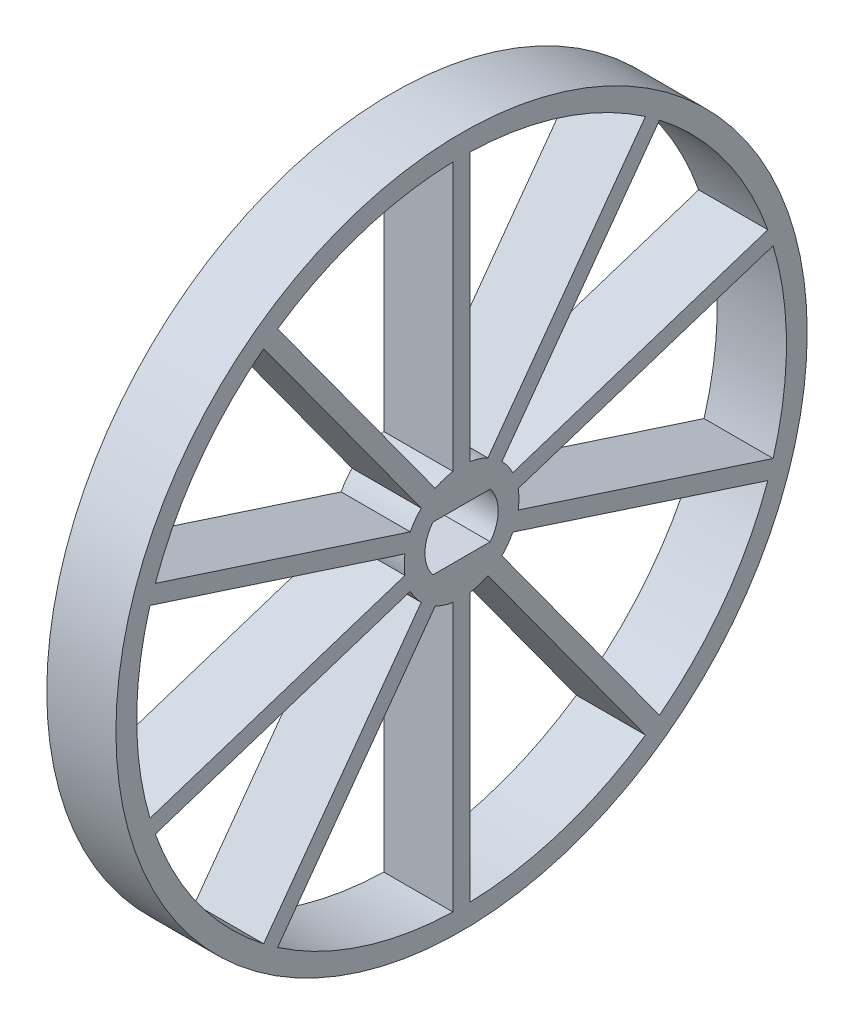
SolidWorks part; units mm, degrees
ref_plane "Front Plane" through (0, 0, 0) normal (0, 0, 1) x (1, 0, 0)
ref_plane "Top Plane" through (0, 0, 0) normal (0, 1, 0) x (1, 0, 0)
ref_plane "Right Plane" through (0, 0, 0) normal (1, 0, 0) x (0, 0, -1)
sketch "Sketch1" plane through (0, 0, 0) normal (1, 0, 0) x (0, 0, -1)
  line L0 (0, 0) -> (0, 27.6652) construction
  line L1 (-2.65, -1.65) -> (2.65, -1.65)
  line L2 (-2.65, -1.65) -> (-2.65, 1.65)
  line L3 (-2.65, 1.65) -> (2.65, 1.65)
  line L4 (2.65, -1.65) -> (2.65, 1.65)
  line L5 (-2.65, -1.65) -> (2.65, 1.65) construction
  line L6 (-2.65, 1.65) -> (2.65, -1.65) construction
  line L8 (-0.625, 3.8326) -> (0.625, 3.8326)
  line L9 (-0.625, 3.8326) -> (-0.625, 23.8326)
  line L10 (-0.625, 23.8326) -> (0.625, 23.8326)
  line L11 (0.625, 3.8326) -> (0.625, 23.8326)
  line L12 (-0.625, 3.8326) -> (0.625, 23.8326) construction
  line L13 (-0.625, 23.8326) -> (0.625, 3.8326) construction
  line L57 (1.7471, 3.468) -> (13.5028, 19.6484)
  line L58 (1.7471, 3.468) -> (2.7584, 2.7333)
  line L59 (2.7584, 2.7333) -> (14.5141, 18.9136)
  line L60 (13.5028, 19.6484) -> (14.5141, 18.9136)
  line L61 (3.4519, 1.7788) -> (22.473, 7.9591)
  line L62 (3.4519, 1.7788) -> (3.8382, 0.5899)
  line L63 (3.8382, 0.5899) -> (22.8593, 6.7703)
  line L64 (22.473, 7.9591) -> (22.8593, 6.7703)
  line L65 (3.8382, -0.5899) -> (22.8593, -6.7703)
  line L66 (3.8382, -0.5899) -> (3.4519, -1.7788)
  line L67 (3.4519, -1.7788) -> (22.473, -7.9591)
  line L68 (22.8593, -6.7703) -> (22.473, -7.9591)
  line L69 (2.7584, -2.7333) -> (14.5141, -18.9136)
  line L70 (2.7584, -2.7333) -> (1.7471, -3.468)
  line L71 (1.7471, -3.468) -> (13.5028, -19.6484)
  line L72 (14.5141, -18.9136) -> (13.5028, -19.6484)
  line L73 (0.625, -3.8326) -> (0.625, -23.8326)
  line L74 (0.625, -3.8326) -> (-0.625, -3.8326)
  line L75 (-0.625, -3.8326) -> (-0.625, -23.8326)
  line L76 (0.625, -23.8326) -> (-0.625, -23.8326)
  line L77 (-1.7471, -3.468) -> (-13.5028, -19.6484)
  line L78 (-1.7471, -3.468) -> (-2.7584, -2.7333)
  line L79 (-2.7584, -2.7333) -> (-14.5141, -18.9136)
  line L80 (-13.5028, -19.6484) -> (-14.5141, -18.9136)
  line L81 (-3.4519, -1.7788) -> (-22.473, -7.9591)
  line L82 (-3.4519, -1.7788) -> (-3.8382, -0.5899)
  line L83 (-3.8382, -0.5899) -> (-22.8593, -6.7703)
  line L84 (-22.473, -7.9591) -> (-22.8593, -6.7703)
  line L85 (-3.8382, 0.5899) -> (-22.8593, 6.7703)
  line L86 (-3.8382, 0.5899) -> (-3.4519, 1.7788)
  line L87 (-3.4519, 1.7788) -> (-22.473, 7.9591)
  line L88 (-22.8593, 6.7703) -> (-22.473, 7.9591)
  line L89 (-2.7584, 2.7333) -> (-14.5141, 18.9136)
  line L90 (-2.7584, 2.7333) -> (-1.7471, 3.468)
  line L91 (-1.7471, 3.468) -> (-13.5028, 19.6484)
  line L92 (-14.5141, 18.9136) -> (-13.5028, 19.6484)
  circle A0 centre (0, 0) radius 2.65
  circle A1 centre (0, 0) radius 4.15
  circle A2 centre (0, 0) radius 25
  circle A3 centre (0, 0) radius 23.5
  point P10 (0, 13.8326)
  point P54 (0, 0)
  point P63 (0, 0)
  dimension "D1" = 5.3
  dimension "D3" = 1.5
  dimension "D4" = 1.5
  dimension "D5" = 50
  dimension "D2" = 3.3
  dimension "D6" = 1.25
  dimension "D7" = 20
  dimension "D8" = 10
extrude "Boss-Extrude2" add sketch "Sketch1" along normal blind 5 contours L11 A3 L9 A1 | A2 A3 L61 L64 L63 L65 L68 L67 L69 L72 L71 L73 L76 L75 L77 L80 L79 L81 L84 L83 L85 L88 L87 L89 L92 L91 L9 L10 L11 L57 L60 L59 | A3 L11 L10 L9 | A3 L91 L92 L89 | L91 A3 L89 A1 | A3 L87 L88 L85 | L87 A3 L85 A1 | A3 L83 L84 L81 | A3 L79 L80 L77 | L79 A3 L77 A1 | L83 A3 L81 A1 | A3 L75 L76 L73 | L75 A3 L73 A1 | A3 L71 L72 L69 | L71 A3 L69 A1 | A3 L67 L68 L65 | L67 A3 L65 A1 | A3 L63 L64 L61 | L63 A3 L61 A1 | A3 L59 L60 L57 | L59 A3 L57 A1 | L83 A1 L81 L82 | L79 A1 L77 L78 | L75 A1 L73 L74 | L71 A1 L69 L70 | L67 A1 L65 L66 | L63 A1 L61 L62 | L59 A1 L57 L58 | L11 A1 L9 L8 | L91 A1 L89 L90 | L87 A1 L85 L86 | L3 A0 | A0 L3 L2 | A0 L2 L1 | L1 A0 | A0 L1 L4 | A0 L4 L3 | L61 A1 L59 L58 L57 L11 L8 L9 L91 L90 L89 L87 L86 L85 L83 L82 L81 L79 L78 L77 L75 L74 L73 L71 L70 L69 L67 L66 L65 L63 L62 A0 L3 L4 L1 L2
